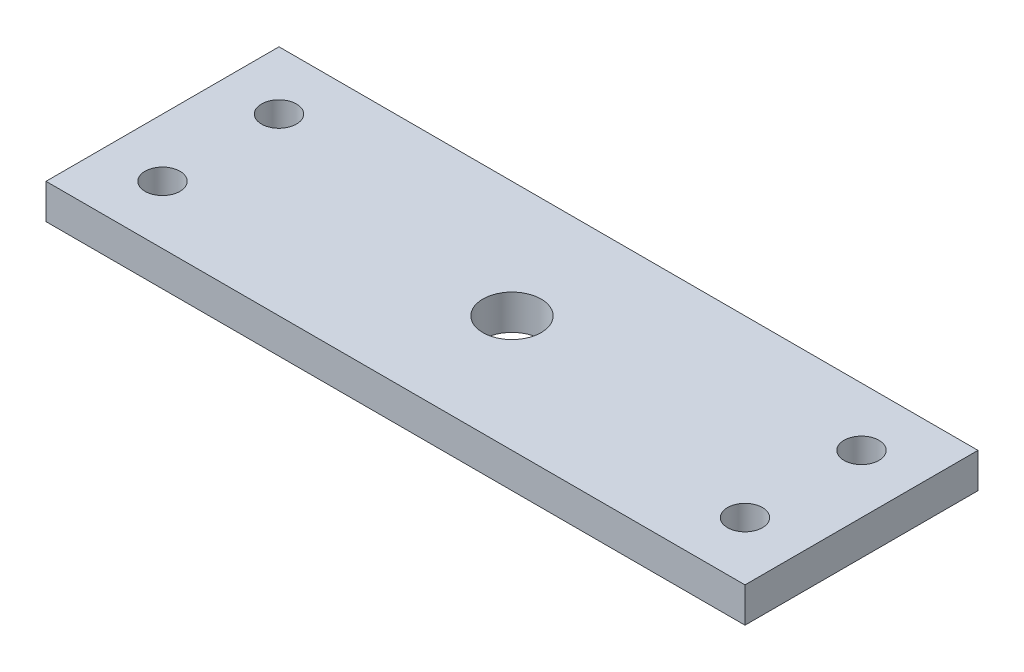
SolidWorks part; units mm, degrees
ref_plane "Płaszczyzna przednia" through (0, 0, 0) normal (0, 0, 1) x (1, 0, 0)
ref_plane "Płaszczyzna górna" through (0, 0, 0) normal (0, 1, 0) x (1, 0, 0)
ref_plane "Płaszczyzna prawa" through (0, 0, 0) normal (1, 0, 0) x (0, 0, -1)
sketch "Sketch1" plane through (0, 0, 0) normal (0, 1, 0) x (1, 0, 0)
  line L0 (-60, 20) -> (0, 0) construction
  line L1 (-60, 20) -> (0, 20)
  line L2 (-60, 20) -> (-60, 0)
  line L3 (-60, 0) -> (0, 0)
  line L4 (0, 20) -> (0, 0)
  line L5 (-30, 35.7498) -> (-30, -18.7848) construction
  line L6 (-69.293, 10) -> (7.6217, 10) construction
  circle A0 centre (-30, 10) radius 2.5
  circle A1 centre (-55, 15) radius 1.5
  circle A2 centre (-55, 5) radius 1.5
  circle A3 centre (-5, 15) radius 1.5
  circle A4 centre (-5, 5) radius 1.5
  point P8 (-30, 10)
  dimension "D3" = 5
  dimension "D4" = 3
  dimension "D1" = 20
  dimension "D2" = 60
  dimension "D5" = 5
  dimension "D6" = 5
extrude "Boss-Extrude1" add sketch "Sketch1" along normal blind 3
